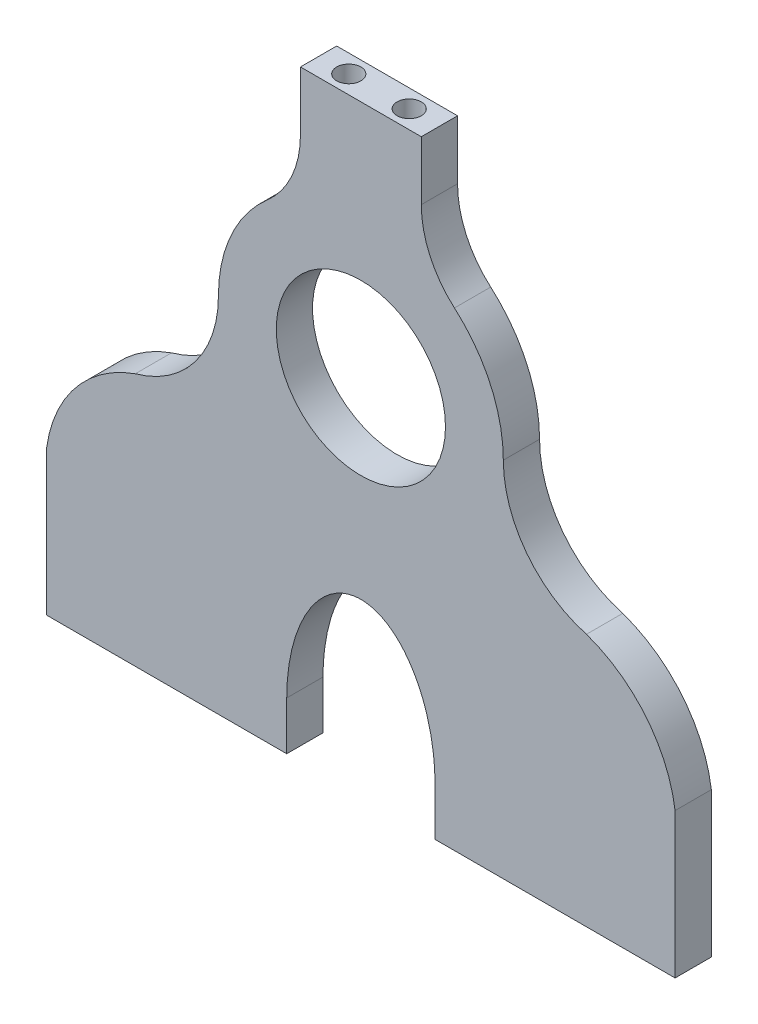
SolidWorks part; units mm, degrees
material "6061-T6 (SS)"
ref_plane "Front Plane" through (0, 0, 0) normal (0, 0, 1) x (1, 0, 0)
ref_plane "Top Plane" through (0, 0, 0) normal (0, 1, 0) x (1, 0, 0)
ref_plane "Right Plane" through (0, 0, 0) normal (1, 0, 0) x (0, 0, -1)
sketch "Sketch1" plane through (0, 0, 0) normal (0, 0, 1) x (1, 0, 0)
  line L0 (22.6432, 59.976) -> (22.6432, -22.574)
  line L1 (-52.1989, -22.574) -> (22.6432, -22.574) construction
  line L2 (-14.7779, -22.574) -> (-14.7779, -28.924) construction
  line L3 (-52.1989, 59.976) -> (-52.1989, -22.574)
  line L4 (-97.3279, -22.574) -> (-97.3279, 2.826)
  line L5 (67.7721, -35.274) -> (-97.3279, -35.274)
  line L6 (67.7721, -35.274) -> (67.7721, -22.574)
  line L7 (67.7721, -22.574) -> (-97.3279, -22.574)
  line L8 (-97.3279, -35.274) -> (-97.3279, -22.574)
  line L9 (67.7721, -35.274) -> (-97.3279, -22.574) construction
  line L10 (67.7721, -22.574) -> (-97.3279, -35.274) construction
  line L11 (67.7721, -22.574) -> (67.7721, 2.826)
  line L12 (-34.2574, -22.574) -> (-34.2574, -35.274)
  line L13 (4.7016, -22.574) -> (4.7016, -35.274)
  line L15 (-30.6529, 71.997) -> (1.0971, 71.997)
  line L16 (-30.6529, 71.997) -> (-30.6529, 122.797)
  line L17 (-30.6529, 122.797) -> (1.0971, 122.797)
  line L18 (1.0971, 71.997) -> (1.0971, 122.797)
  line L19 (-30.6529, 71.997) -> (1.0971, 122.797) construction
  line L20 (-30.6529, 122.797) -> (1.0971, 71.997) construction
  circle A0 centre (-14.7779, 59.976) radius 19.6182
  circle A1 centre (-14.7779, 59.976) radius 37.4211
  arc A2 (-97.3279, 2.826) -> (-74.0454, 31.2883) centre (-62.4213, -1.9741) cw
  arc A3 (-74.0454, 31.2883) -> (-52.1989, 59.976) centre (-81.9577, 59.976) ccw
  arc A4 (44.4897, 31.2883) -> (22.6432, 59.976) centre (52.402, 59.976) cw
  arc A5 (67.7721, 2.826) -> (44.4897, 31.2883) centre (32.8656, -1.9741) ccw
  ellipse E0 centre (-14.7779, -22.574) end of major axis (-14.7779, -54.7435) minor radius 19.4795
  point P13 (-14.7779, 97.397)
  point P31 (-14.7779, 97.397)
  dimension "D1" = 12.7
  dimension "D7" = 95.25
  dimension "D2" = 165.1
  dimension "D3" = 6.35
  dimension "D4" = 25.4
  dimension "D5" = 31.75
  dimension "D6" = 50.8
extrude "Boss-Extrude1" add sketch "Sketch1" along normal blind 3.175 contours A1 L3 L7 L0 | A1 A0 | L18 A1 L16 L15 A0 | A1 L18 L17 L16 | A3 A2 L4 L7 L3 | L11 A5 A4 L0 L7 | L7 L13 L5 L6 | L12 L7 L8 L5
fillet "Fillet1" radius 25.4 2 edges at (-30.6529, 93.8628, 1.5875) (1.0971, 93.8628, 1.5875)
sketch "Sketch2" plane through (0, 0, 3.175) normal (0, 0, 1) x (1, 0, 0)
  line L9 (1.0971, 107.3348) -> (1.0971, 122.797)
  line L10 (1.0971, 122.797) -> (-30.6529, 122.797)
  line L11 (-30.6529, 122.797) -> (-30.6529, 107.3348)
  line L12 (-97.3279, 2.826) -> (-97.3279, -35.274)
  line L13 (-97.3279, -35.274) -> (-34.2574, -35.274)
  line L14 (-34.2574, -35.274) -> (-34.2574, -22.574)
  line L15 (4.7016, -22.574) -> (4.7016, -35.274)
  line L16 (4.7016, -35.274) -> (67.7721, -35.274)
  line L17 (67.7721, -35.274) -> (67.7721, 2.826)
  line L18 (1.0971, 107.3348) -> (1.0971, 122.797)
  line L19 (1.0971, 122.797) -> (-30.6529, 122.797)
  line L20 (-30.6529, 122.797) -> (-30.6529, 107.3348)
  line L21 (-97.3279, 2.826) -> (-97.3279, -35.274)
  line L22 (-97.3279, -35.274) -> (-34.2574, -35.274)
  line L23 (-34.2574, -35.274) -> (-34.2574, -22.574)
  line L24 (4.7016, -22.574) -> (4.7016, -35.274)
  line L25 (4.7016, -35.274) -> (67.7721, -35.274)
  line L26 (67.7721, -35.274) -> (67.7721, 2.826)
  circle A0 centre (-14.7779, 59.976) radius 15.875
  arc A8 (22.6432, 59.976) -> (9.8087, 88.1865) centre (-14.7779, 59.976) ccw
  arc A9 (1.0971, 107.3348) -> (9.8087, 88.1865) centre (26.4971, 107.3348) ccw
  arc A10 (-39.3644, 88.1865) -> (-30.6529, 107.3348) centre (-56.0529, 107.3348) ccw
  arc A11 (-39.3644, 88.1865) -> (-52.1989, 59.976) centre (-14.7779, 59.976) ccw
  arc A12 (-74.0454, 31.2883) -> (-52.1989, 59.976) centre (-81.9577, 59.976) ccw
  arc A13 (-74.0454, 31.2883) -> (-97.3279, 2.826) centre (-62.4213, -1.9741) ccw
  arc A14 (67.7721, 2.826) -> (44.4897, 31.2883) centre (32.8656, -1.9741) ccw
  arc A15 (22.6432, 59.976) -> (44.4897, 31.2883) centre (52.402, 59.976) ccw
  arc A16 (22.6432, 59.976) -> (9.8087, 88.1865) centre (-14.7779, 59.976) ccw
  arc A17 (1.0971, 107.3348) -> (9.8087, 88.1865) centre (26.4971, 107.3348) ccw
  arc A18 (-39.3644, 88.1865) -> (-30.6529, 107.3348) centre (-56.0529, 107.3348) ccw
  arc A19 (-39.3644, 88.1865) -> (-52.1989, 59.976) centre (-14.7779, 59.976) ccw
  arc A20 (-74.0454, 31.2883) -> (-52.1989, 59.976) centre (-81.9577, 59.976) ccw
  arc A21 (-74.0454, 31.2883) -> (-97.3279, 2.826) centre (-62.4213, -1.9741) ccw
  arc A22 (67.7721, 2.826) -> (44.4897, 31.2883) centre (32.8656, -1.9741) ccw
  arc A23 (22.6432, 59.976) -> (44.4897, 31.2883) centre (52.402, 59.976) ccw
  ellipse E1 centre (-14.7779, -22.574) end of major axis (-14.7779, -54.7435) minor radius 19.4795 (4.7016, -22.574) -> (-34.2574, -22.574) ccw
  ellipse E2 centre (-14.7779, -22.574) end of major axis (-14.7779, -54.7435) minor radius 19.4795 (4.7016, -22.574) -> (-34.2574, -22.574) ccw
  dimension "D2" = 31.75
  dimension "D1" = 0
extrude "Boss-Extrude2" add sketch "Sketch2" along normal blind 12.7
sketch "Sketch5" plane through (0, 0, 15.875) normal (0, 0, 1) x (1, 0, 0)
  line L9 (1.0971, 107.3348) -> (1.0971, 122.797)
  line L10 (1.0971, 122.797) -> (-30.6529, 122.797)
  line L11 (-30.6529, 122.797) -> (-30.6529, 107.3348)
  line L12 (-97.3279, 2.826) -> (-97.3279, -35.274)
  line L13 (-97.3279, -35.274) -> (-34.2574, -35.274)
  line L14 (-34.2574, -35.274) -> (-34.2574, -22.574)
  line L15 (4.7016, -22.574) -> (4.7016, -35.274)
  line L16 (4.7016, -35.274) -> (67.7721, -35.274)
  line L17 (67.7721, -35.274) -> (67.7721, 2.826)
  line L18 (1.0971, 107.3348) -> (1.0971, 122.797)
  line L19 (1.0971, 122.797) -> (-30.6529, 122.797)
  line L20 (-30.6529, 122.797) -> (-30.6529, 107.3348)
  line L21 (-97.3279, 2.826) -> (-97.3279, -35.274)
  line L22 (-97.3279, -35.274) -> (-34.2574, -35.274)
  line L23 (-34.2574, -35.274) -> (-34.2574, -22.574)
  line L24 (4.7016, -22.574) -> (4.7016, -35.274)
  line L25 (4.7016, -35.274) -> (67.7721, -35.274)
  line L26 (67.7721, -35.274) -> (67.7721, 2.826)
  circle A0 centre (-14.7779, 59.976) radius 15.875
  arc A8 (22.6432, 59.976) -> (44.4897, 31.2883) centre (52.402, 59.976) ccw
  arc A9 (22.6432, 59.976) -> (9.8087, 88.1865) centre (-14.7779, 59.976) ccw
  arc A10 (1.0971, 107.3348) -> (9.8087, 88.1865) centre (26.4971, 107.3348) ccw
  arc A11 (-39.3644, 88.1865) -> (-30.6529, 107.3348) centre (-56.0529, 107.3348) ccw
  arc A12 (-39.3644, 88.1865) -> (-52.1989, 59.976) centre (-14.7779, 59.976) ccw
  arc A13 (-74.0454, 31.2883) -> (-52.1989, 59.976) centre (-81.9577, 59.976) ccw
  arc A14 (-74.0454, 31.2883) -> (-97.3279, 2.826) centre (-62.4213, -1.9741) ccw
  arc A15 (67.7721, 2.826) -> (44.4897, 31.2883) centre (32.8656, -1.9741) ccw
  arc A16 (22.6432, 59.976) -> (44.4897, 31.2883) centre (52.402, 59.976) ccw
  arc A17 (22.6432, 59.976) -> (9.8087, 88.1865) centre (-14.7779, 59.976) ccw
  arc A18 (1.0971, 107.3348) -> (9.8087, 88.1865) centre (26.4971, 107.3348) ccw
  arc A19 (-39.3644, 88.1865) -> (-30.6529, 107.3348) centre (-56.0529, 107.3348) ccw
  arc A20 (-39.3644, 88.1865) -> (-52.1989, 59.976) centre (-14.7779, 59.976) ccw
  arc A21 (-74.0454, 31.2883) -> (-52.1989, 59.976) centre (-81.9577, 59.976) ccw
  arc A22 (-74.0454, 31.2883) -> (-97.3279, 2.826) centre (-62.4213, -1.9741) ccw
  arc A23 (67.7721, 2.826) -> (44.4897, 31.2883) centre (32.8656, -1.9741) ccw
  ellipse E1 centre (-14.7779, -22.574) end of major axis (-14.7779, -54.7435) minor radius 19.4795 (4.7016, -22.574) -> (-34.2574, -22.574) ccw
  ellipse E2 centre (-14.7779, -22.574) end of major axis (-14.7779, -54.7435) minor radius 19.4795 (4.7016, -22.574) -> (-34.2574, -22.574) ccw
  dimension "D1" = 0
extrude "Cut-Extrude3" cut sketch "Sketch5" against normal blind 6.35
sketch "Sketch3" plane through (0, -35.274, 0) normal (0, -1, 0) x (1, 0, 0)
  line L1 (-65.7926, 9.525) -> (-65.7926, 0) construction
  line L2 (-34.2574, 0) -> (-97.3279, 0) construction
  line L3 (-65.7926, 4.7625) -> (-97.3279, 4.7625) construction
  line L5 (-65.7926, 4.7625) -> (-34.2574, 4.7625) construction
  line L6 (-97.3279, 9.525) -> (-34.2574, 9.525) construction
  line L7 (-34.2574, 4.7625) -> (4.7016, 4.7625) construction
  line L9 (-14.7779, 7.9375) -> (-14.7779, 35.4299) construction
  circle A0 centre (-50.025, 4.7625) radius 3.175
  circle A1 centre (-81.5603, 4.7625) radius 3.175
  circle A2 centre (20.4693, 4.7625) radius 3.175
  circle A3 centre (52.0045, 4.7625) radius 3.175
  dimension "D1" = 6.35
  dimension "D2" = 6.35
extrude "Cut-Extrude1" cut sketch "Sketch3" against normal blind 12.7
sketch "Sketch4" plane through (0, 122.797, 0) normal (0, 1, 0) x (1, 0, 0)
  line L0 (-30.6529, 0) -> (1.0971, 0) construction
  line L2 (-14.7779, 0) -> (-14.7779, -9.525) construction
  line L5 (-30.6529, 0) -> (-30.6529, -9.525) construction
  line L6 (-30.6529, -4.7625) -> (-14.7779, -4.7625) construction
  line L7 (-14.7779, -4.7625) -> (1.0971, -4.7625) construction
  line L8 (1.0971, -9.525) -> (1.0971, 0) construction
  circle A0 centre (-22.7154, -4.7625) radius 3.175
  circle A1 centre (-6.8404, -4.7625) radius 3.175
  dimension "D1" = 6.35
  dimension "D2" = 6.35
extrude "Cut-Extrude2" cut sketch "Sketch4" against normal blind 12.7
sketch "Sketch7" plane through (0, 0, 9.525) normal (0, 0, 1) x (1, 0, 0)
  circle A0 centre (-14.7779, 59.976) radius 15.875
  circle A1 centre (-14.7779, 59.976) radius 22.225
  dimension "D1" = 31.75
  dimension "D2" = 6.35
extrude "Cut-Extrude4" cut sketch "Sketch7" against normal blind 23.876
